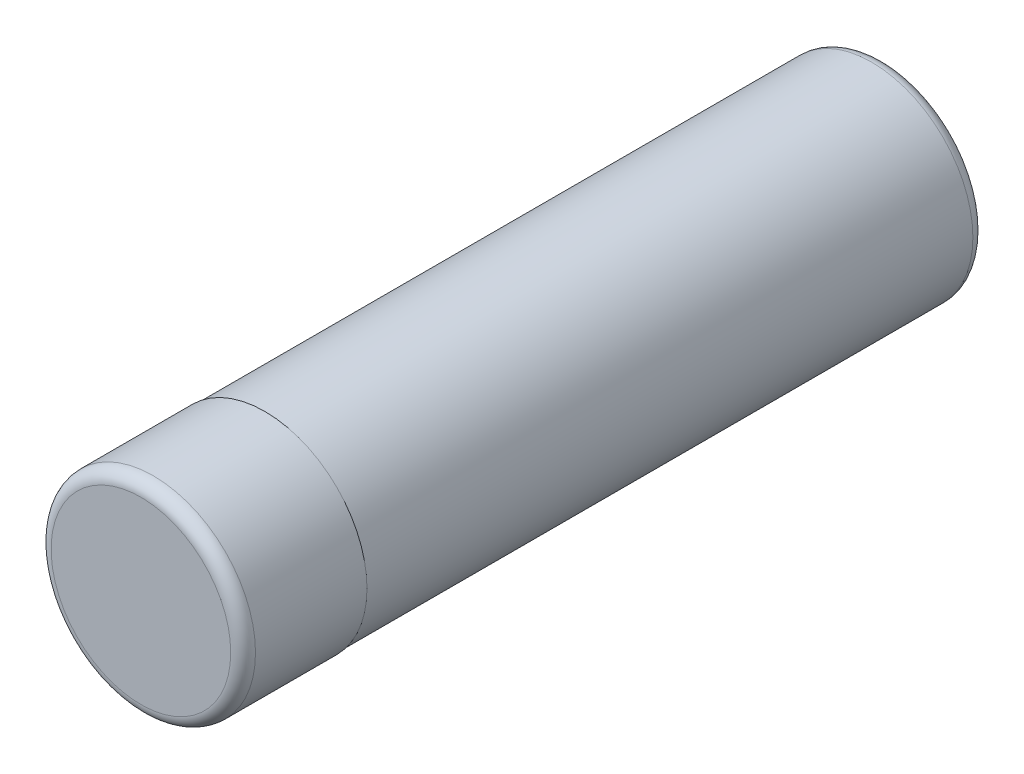
SolidWorks part; units mm, degrees
ref_plane "정면" through (0, 0, 0) normal (0, 0, 1) x (1, 0, 0)
ref_plane "윗면" through (0, 0, 0) normal (0, 1, 0) x (1, 0, 0)
ref_plane "우측면" through (0, 0, 0) normal (1, 0, 0) x (0, 0, -1)
sketch "스케치1" plane through (0, 0, 0) normal (0, 0, 1) x (1, 0, 0)
  circle A0 centre (0, 0) radius 2.45
  dimension "D1" = 4.9
extrude "보스-돌출1" add sketch "스케치1" along normal blind 15
sketch "스케치2" plane through (0, 0, 15) normal (0, 0, 1) x (1, 0, 0)
  circle A0 centre (0, 0) radius 2.475
  dimension "D1" = 4.95
extrude "보스-돌출2" add sketch "스케치2" along normal blind 3
fillet "필렛1" radius 0.3 1 edges at (2.475, 0, 18)
fillet "필렛2" radius 0.3 1 edges at (2.45, 0, 0)
